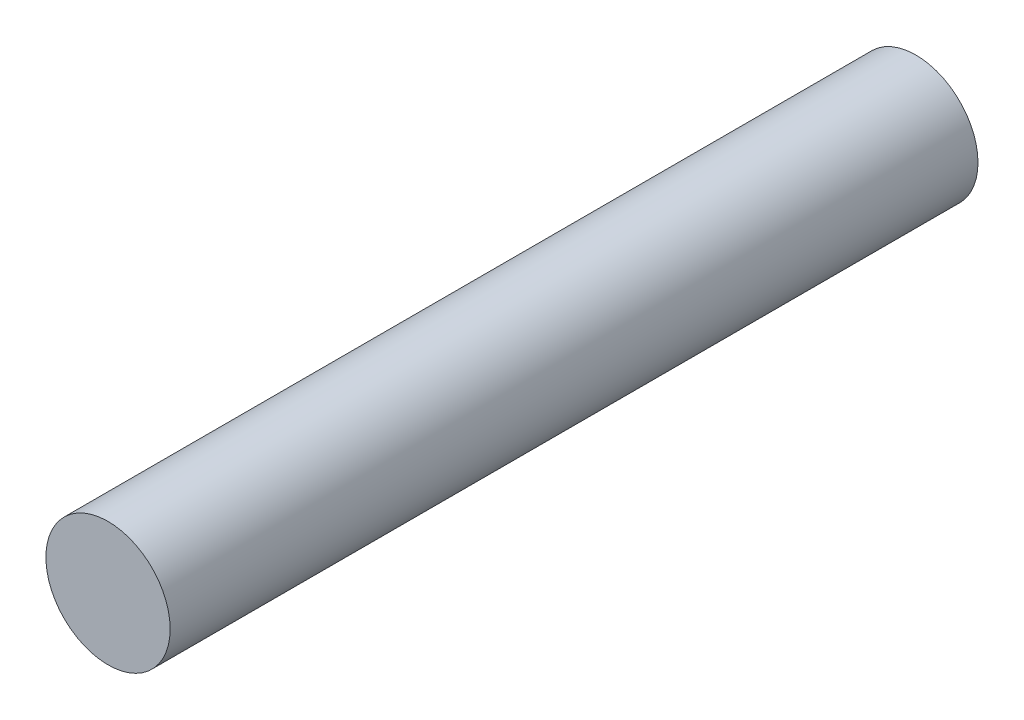
SolidWorks part; units mm, degrees
material "Q235-A"
ref_plane "前视基准面" through (0, 0, 0) normal (0, 0, 1) x (1, 0, 0)
ref_plane "上视基准面" through (0, 0, 0) normal (0, 1, 0) x (1, 0, 0)
ref_plane "右视基准面" through (0, 0, 0) normal (1, 0, 0) x (0, 0, -1)
sketch "草图1" plane through (0, 0, 0) normal (0, 0, 1) x (1, 0, 0)
  circle A1 centre (0, 0) radius 10
  dimension "D1" = 20
extrude "凸台-拉伸1" add sketch "草图1" along normal blind 130
